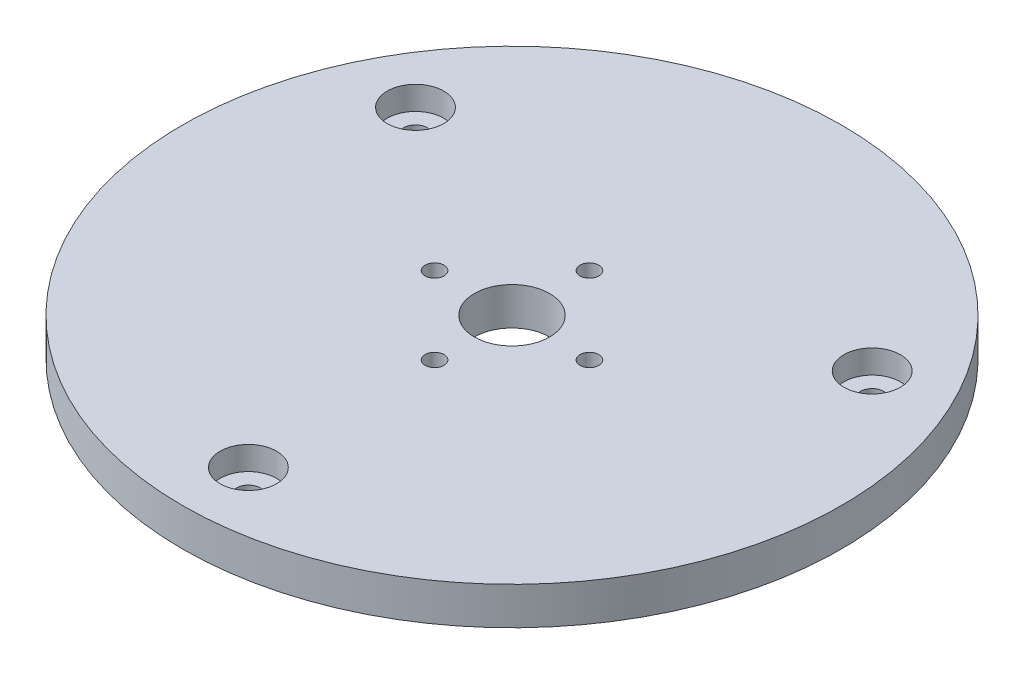
SolidWorks part; units mm, degrees
ref_plane "Front Plane" through (0, 0, 0) normal (0, 0, 1) x (1, 0, 0)
ref_plane "Top Plane" through (0, 0, 0) normal (0, 1, 0) x (1, 0, 0)
ref_plane "Right Plane" through (0, 0, 0) normal (1, 0, 0) x (0, 0, -1)
sketch "Sketch1" plane through (0, 0, 0) normal (0, 1, 0) x (1, 0, 0)
  circle A0 centre (0, 0) radius 35
  dimension "D1" = 70
extrude "Boss-Extrude1" add sketch "Sketch1" along normal blind 4 contours A0
sketch "Sketch2" plane through (0, 4, 0) normal (0, 1, 0) x (1, 0, 0)
  circle A2 centre (0, 8.2271) radius 1
  circle A3 centre (8.2271, 0) radius 1
  circle A4 centre (0, -8.2271) radius 1
  circle A5 centre (-8.2271, 0) radius 1
  circle A7 centre (0, -28) radius 1.25
  circle A8 centre (-24.2487, 14) radius 1.25
  circle A9 centre (24.2487, 14) radius 1.25
  dimension "D2" = 4
  dimension "D3" = 3
extrude "Cut-Extrude1" cut sketch "Sketch2" against normal through all
sketch "Sketch3" plane through (0, 0, 0) normal (0, -1, 0) x (1, 0, 0)
  circle A0 centre (0, 0) radius 4
  dimension "D1" = 8
extrude "Cut-Extrude2" cut sketch "Sketch3" against normal up to next
sketch "Sketch4" plane through (0, 4, 0) normal (0, 1, 0) x (1, 0, 0)
  circle A0 centre (24.2487, 14) radius 3
  circle A1 centre (0, -28) radius 3
  circle A2 centre (-24.2487, 14) radius 3
  dimension "D1" = 6
  dimension "D2" = 3
extrude "Cut-Extrude3" cut sketch "Sketch4" against normal blind 2.5
sketch "Sketch5" plane through (0, 0, 0) normal (0, -1, 0) x (1, 0, 0)
  circle A0 centre (0, 8.2271) radius 2
  circle A1 centre (8.2271, 0) radius 2
  circle A2 centre (0, -8.2271) radius 2
  circle A3 centre (-8.2271, 0) radius 2
  dimension "D1" = 4
  dimension "D2" = 4
extrude "Cut-Extrude4" cut sketch "Sketch5" against normal blind 2.5
